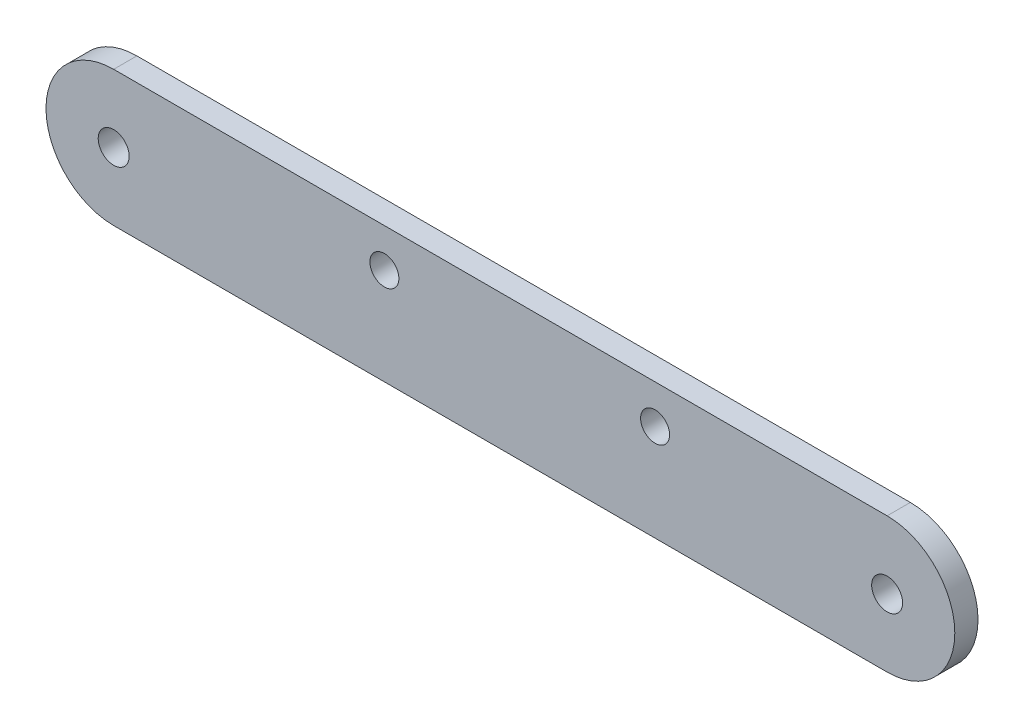
SolidWorks part; units mm, degrees
ref_plane "Plan de face" through (0, 0, 0) normal (0, 0, 1) x (1, 0, 0)
ref_plane "Plan de dessus" through (0, 0, 0) normal (0, 1, 0) x (1, 0, 0)
ref_plane "Plan de droite" through (0, 0, 0) normal (1, 0, 0) x (0, 0, -1)
sketch "Esquisse1" plane through (0, 0, 0) normal (0, 0, 1) x (1, 0, 0)
  line L0 (-114.1184, 0) -> (85.8816, 0) construction
  line L1 (-114.1184, 17.5) -> (85.8816, 17.5)
  line L2 (-114.1184, -17.5) -> (85.8816, -17.5)
  arc A0 (-114.1184, 17.5) -> (-114.1184, -17.5) centre (-114.1184, 0) ccw
  arc A1 (85.8816, -17.5) -> (85.8816, 17.5) centre (85.8816, 0) ccw
  circle A2 centre (-114.1184, 0) radius 4
  circle A3 centre (85.8816, 0) radius 4
  point P3 (-14.1184, 0)
  dimension "D3" = 8
  dimension "D1" = 35
  dimension "D2" = 200
extrude "Boss.-Extru.1" add sketch "Esquisse1" along normal blind 6
sketch "Esquisse2" plane through (0, 0, 6) normal (0, 0, 1) x (1, 0, 0)
  line L0 (85.8816, 17.5) -> (-114.1184, 17.5) construction
  circle A0 centre (-44.1184, 7.5) radius 3.75
  circle A1 centre (25.8816, 7.5) radius 3.75
  circle A2 centre (-114.1184, 0) radius 4 construction
  point P8 (0, 0)
  dimension "D1" = 7.5
  dimension "D4" = 70
  dimension "D2" = 10
  dimension "D3" = 70
extrude "Enlèv. mat.-Extru.1" cut sketch "Esquisse2" against normal up to next
